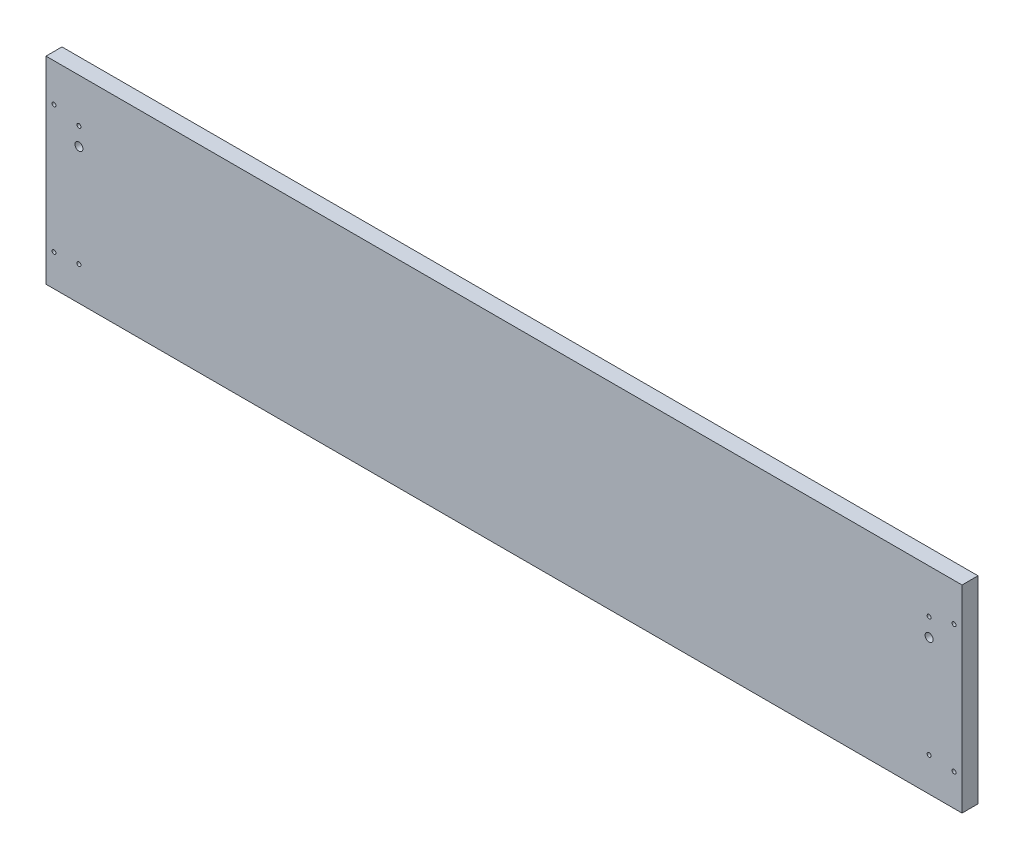
SolidWorks part; units mm, degrees
material "Pine"
ref_plane "Front Plane" through (0, 0, 0) normal (0, 0, 1) x (1, 0, 0)
ref_plane "Top Plane" through (0, 0, 0) normal (0, 1, 0) x (1, 0, 0)
ref_plane "Right Plane" through (0, 0, 0) normal (1, 0, 0) x (0, 0, -1)
sketch "Sketch1" plane through (0, 0, 0) normal (0, 0, 1) x (1, 0, 0)
  line L0 (-5300.6625, 1520.825) -> (-5451.475, 1520.825)
  line L1 (-5456.2375, 1384.3) -> (-5456.2375, 1516.0625)
  line L2 (-5557.8375, 1546.225) -> (-5194.3, 1546.225)
  line L3 (-5557.8375, 1539.875) -> (-5194.3, 1539.875)
  line L4 (-5297.4875, 1377.95) -> (-5454.65, 1377.95)
  line L5 (-5291.1375, 1384.3) -> (-5291.1375, 1516.0625)
  line L6 (-5300.6625, 1525.5875) -> (-5451.475, 1525.5875)
  line L7 (-5461, 1384.3) -> (-5461, 1516.0625)
  line L8 (-5297.4875, 1382.7125) -> (-5454.65, 1382.7125)
  line L9 (-5295.9, 1384.3) -> (-5295.9, 1516.0625)
  line L10 (-5740.4, 998.5375) -> (-5740.4, 1181.1)
  line L11 (-5740.4, 1181.1) -> (-5512.5938, 1181.1)
  line L12 (-5512.5938, 1181.1) -> (-5512.5938, 998.5375)
  line L13 (-5512.5938, 998.5375) -> (-5740.4, 998.5375)
  line L14 (-5258.5938, 1181.1) -> (-5486.4, 1181.1)
  line L15 (-5258.5938, 998.5375) -> (-5258.5938, 1181.1)
  line L16 (-5486.4, 998.5375) -> (-5258.5938, 998.5375)
  line L17 (-5486.4, 1181.1) -> (-5486.4, 998.5375)
  line L18 (-5740.4, 898.525) -> (-5011.7375, 898.525)
  line L19 (-5168.1062, 1384.3) -> (-5168.1062, 1392.2375)
  line L20 (-5176.0437, 1400.175) -> (-5245.8937, 1400.175)
  line L21 (-5253.8313, 1392.2375) -> (-5253.8313, 1384.3)
  line L22 (-5451.475, 1512.8875) -> (-5451.475, 1384.3)
  line L23 (-5303.8375, 1516.0625) -> (-5448.3, 1516.0625)
  line L24 (-5498.3062, 1384.3) -> (-5451.475, 1384.3)
  line L25 (-5253.8313, 1384.3) -> (-5300.6625, 1384.3)
  line L26 (-5584.0312, 1384.3) -> (-5740.4, 1384.3)
  line L27 (-5564.1875, 1536.7) -> (-5740.4, 1536.7)
  line L28 (-5740.4, 1357.3125) -> (-5740.4, 1206.5)
  line L29 (-5011.7375, 1357.3125) -> (-5740.4, 1357.3125)
  line L30 (-5011.7375, 1206.5) -> (-5011.7375, 1357.3125)
  line L31 (-5740.4, 1206.5) -> (-5011.7375, 1206.5)
  line L32 (-4765.675, 1549.4) -> (-4978.4, 1549.4)
  line L33 (-4765.675, 1397) -> (-4765.675, 1549.4)
  line L34 (-4978.4, 1397) -> (-4765.675, 1397)
  line L35 (-4978.4, 1549.4) -> (-4978.4, 1397)
  line L36 (-4765.675, 1371.6) -> (-4978.4, 1371.6)
  line L37 (-4765.675, 1219.2) -> (-4765.675, 1371.6)
  line L38 (-4978.4, 1219.2) -> (-4765.675, 1219.2)
  line L39 (-4978.4, 1371.6) -> (-4978.4, 1219.2)
  line L40 (-5284.7875, 803.275) -> (-5272.0875, 803.275)
  line L41 (-5187.95, 1536.7) -> (-5011.7375, 1536.7)
  line L42 (-5300.6625, 1384.3) -> (-5300.6625, 1512.8875)
  line L43 (-5740.4, 1536.7) -> (-5740.4, 1384.3)
  line L44 (-5557.8375, 1536.7) -> (-5557.8375, 1549.4)
  line L45 (-5557.8375, 1549.4) -> (-5194.3, 1549.4)
  line L46 (-5194.3, 1549.4) -> (-5194.3, 1536.7)
  line L47 (-5011.7375, 1536.7) -> (-5011.7375, 1384.3)
  line L48 (-5011.7375, 1384.3) -> (-5168.1062, 1384.3)
  line L49 (-5498.3062, 1384.3) -> (-5498.3062, 1392.2375)
  line L50 (-5506.2437, 1400.175) -> (-5576.0938, 1400.175)
  line L51 (-5584.0312, 1392.2375) -> (-5584.0312, 1384.3)
  line L52 (-5740.4, 660.4) -> (-5740.4, 898.525)
  line L53 (-5011.7375, 898.525) -> (-5011.7375, 660.4)
  line L54 (-5011.7375, 660.4) -> (-5740.4, 660.4)
  line L55 (-5291.1375, 803.275) -> (-5291.1375, 752.475)
  line L56 (-5265.7375, 752.475) -> (-5265.7375, 803.275)
  line L57 (-5284.7875, 752.475) -> (-5272.0875, 752.475)
  arc A0 (-5451.475, 1520.825) -> (-5456.2375, 1516.0625) centre (-5451.475, 1516.0625) ccw
  arc A1 (-5461, 1384.3) -> (-5454.65, 1377.95) centre (-5454.65, 1384.3) ccw
  arc A2 (-5297.4875, 1377.95) -> (-5291.1375, 1384.3) centre (-5297.4875, 1384.3) ccw
  circle A3 centre (-5037.9312, 1233.4875) radius 1.5875
  circle A4 centre (-5037.9312, 1328.7375) radius 1.5875
  circle A5 centre (-5714.2063, 1233.4875) radius 1.5875
  circle A6 centre (-5714.2063, 1328.7375) radius 1.5875
  circle A7 centre (-5018.0875, 1333.5) radius 1.5875
  circle A8 centre (-5018.0875, 1231.9) radius 1.5875
  circle A9 centre (-5734.05, 1231.9) radius 1.5875
  circle A10 centre (-5734.05, 1333.5) radius 1.5875
  circle A11 centre (-5734.05, 1511.3) radius 1.5875
  circle A12 centre (-5734.05, 1409.7) radius 1.5875
  circle A13 centre (-5018.0875, 1511.3) radius 1.5875
  circle A14 centre (-5018.0875, 1409.7) radius 1.5875
  arc A15 (-5557.8375, 1546.225) -> (-5557.8375, 1539.875) centre (-5557.8375, 1543.05) ccw
  arc A16 (-5194.3, 1539.875) -> (-5194.3, 1546.225) centre (-5194.3, 1543.05) ccw
  arc A17 (-5291.1375, 1516.0625) -> (-5300.6625, 1525.5875) centre (-5300.6625, 1516.0625) ccw
  arc A18 (-5451.475, 1525.5875) -> (-5461, 1516.0625) centre (-5451.475, 1516.0625) ccw
  arc A19 (-5456.2375, 1384.3) -> (-5454.65, 1382.7125) centre (-5454.65, 1384.3) ccw
  arc A20 (-5297.4875, 1382.7125) -> (-5295.9, 1384.3) centre (-5297.4875, 1384.3) ccw
  arc A21 (-5295.9, 1516.0625) -> (-5300.6625, 1520.825) centre (-5300.6625, 1516.0625) ccw
  circle A22 centre (-5702.3, 892.175) radius 1.5875
  circle A23 centre (-5734.05, 860.425) radius 1.5875
  circle A24 centre (-5474.8906, 892.175) radius 1.5875
  circle A25 centre (-5277.2469, 892.175) radius 1.5875
  circle A26 centre (-5049.8375, 892.175) radius 1.5875
  circle A27 centre (-5018.0875, 860.425) radius 1.5875
  circle A28 centre (-5296.6938, 1174.75) radius 1.5875
  circle A29 centre (-5448.3, 1174.75) radius 1.5875
  circle A30 centre (-5264.9437, 1155.7) radius 1.5875
  circle A31 centre (-5264.9437, 1023.9375) radius 1.5875
  circle A32 centre (-5518.9438, 1155.7) radius 1.5875
  circle A33 centre (-5518.9438, 1023.9375) radius 1.5875
  circle A34 centre (-5702.3, 1004.8875) radius 1.5875
  circle A35 centre (-5550.6937, 1004.8875) radius 1.5875
  arc A36 (-5576.0938, 1400.175) -> (-5584.0312, 1392.2375) centre (-5576.0938, 1392.2375) ccw
  arc A37 (-5168.1062, 1392.2375) -> (-5176.0437, 1400.175) centre (-5176.0437, 1392.2375) ccw
  arc A38 (-5245.8937, 1400.175) -> (-5253.8313, 1392.2375) centre (-5245.8937, 1392.2375) ccw
  arc A39 (-5448.3, 1516.0625) -> (-5451.475, 1512.8875) centre (-5448.3, 1512.8875) ccw
  arc A40 (-5284.7875, 803.275) -> (-5291.1375, 803.275) centre (-5287.9625, 803.275) ccw
  circle A41 centre (-5679.2812, 1026.3187) radius 1.5875
  circle A42 centre (-5679.2812, 1153.3187) radius 1.5875
  circle A43 centre (-5571.3313, 1153.3187) radius 1.5875
  circle A44 centre (-5571.3313, 1026.3187) radius 1.5875
  circle A45 centre (-5317.3312, 1153.3187) radius 1.5875
  circle A46 centre (-5317.3312, 1026.3187) radius 1.5875
  circle A47 centre (-5425.2812, 1026.3187) radius 1.5875
  circle A48 centre (-5425.2812, 1153.3187) radius 1.5875
  arc A49 (-5194.3, 1536.7) -> (-5187.95, 1536.7) centre (-5191.125, 1536.7) ccw
  arc A50 (-5564.1875, 1536.7) -> (-5557.8375, 1536.7) centre (-5561.0125, 1536.7) ccw
  arc A51 (-5300.6625, 1512.8875) -> (-5303.8375, 1516.0625) centre (-5303.8375, 1512.8875) ccw
  arc A52 (-5498.3062, 1392.2375) -> (-5506.2437, 1400.175) centre (-5506.2437, 1392.2375) ccw
  circle A53 centre (-5712.46, 784.225) radius 4.7625
  arc A54 (-5272.0875, 752.475) -> (-5265.7375, 752.475) centre (-5268.9125, 752.475) ccw
  arc A55 (-5291.1375, 752.475) -> (-5284.7875, 752.475) centre (-5287.9625, 752.475) ccw
  circle A56 centre (-5182.3938, 684.2125) radius 3.175
  circle A57 centre (-5239.5437, 684.2125) radius 3.175
  circle A58 centre (-5512.5938, 684.2125) radius 3.175
  circle A59 centre (-5569.7437, 684.2125) radius 3.175
  circle A60 centre (-5474.8906, 666.75) radius 1.5875
  circle A61 centre (-5277.2469, 666.75) radius 1.5875
  circle A62 centre (-5734.05, 698.5) radius 1.5875
  circle A63 centre (-5702.3, 666.75) radius 1.5875
  circle A64 centre (-5049.8375, 666.75) radius 1.5875
  circle A65 centre (-5018.0875, 698.5) radius 1.5875
  circle A66 centre (-5713.73, 835.025) radius 4.7625
  circle A67 centre (-5712.46, 819.785) radius 4.7625
  circle A68 centre (-5712.46, 802.005) radius 4.7625
  circle A69 centre (-5714.2063, 1314.45) radius 3.175
  circle A70 centre (-5037.9312, 1314.45) radius 3.175
  arc A71 (-5265.7375, 803.275) -> (-5272.0875, 803.275) centre (-5268.9125, 803.275) ccw
  ellipse E0 centre (-5371.3062, 1089.8188) end of major axis (-5277.6438, 1089.8188) minor radius 65.0875
  ellipse E1 centre (-5625.3062, 1089.8188) end of major axis (-5531.6438, 1089.8188) minor radius 65.0875
sketch "Sketch2" plane through (0, 0, 0) normal (0, 0, 1) x (1, 0, 0)
  line L0 (-5011.7375, 1206.5) -> (-5011.7375, 1363.6625)
  line L1 (-5011.7375, 1363.6625) -> (-5740.4, 1363.6625)
  line L2 (-5740.4, 1363.6625) -> (-5740.4, 1206.5)
  line L3 (-5740.4, 1206.5) -> (-5011.7375, 1206.5)
  dimension "D1" = 157.1625
extrude "Extrude1" add sketch "Sketch2" against normal blind 12.7
sketch "Sketch3" plane through (0, 0, 0) normal (0, 0, 1) x (1, 0, 0)
  circle A0 centre (-5714.2063, 1314.45) radius 3.175
  circle A1 centre (-5714.2063, 1328.7375) radius 1.5875
  circle A2 centre (-5734.05, 1333.5) radius 1.5875
  circle A3 centre (-5734.05, 1231.9) radius 1.5875
  circle A4 centre (-5714.2063, 1233.4875) radius 1.5875
  circle A5 centre (-5037.9312, 1314.45) radius 3.175
  circle A6 centre (-5037.9312, 1328.7375) radius 1.5875
  circle A7 centre (-5018.0875, 1333.5) radius 1.5875
  circle A8 centre (-5037.9312, 1233.4875) radius 1.5875
  circle A9 centre (-5018.0875, 1231.9) radius 1.5875
extrude "Cut-Extrude1" cut sketch "Sketch3" against normal up to surface (12.7 mm away) up to face at (-5376.0688, 1285.0812, -12.7)
